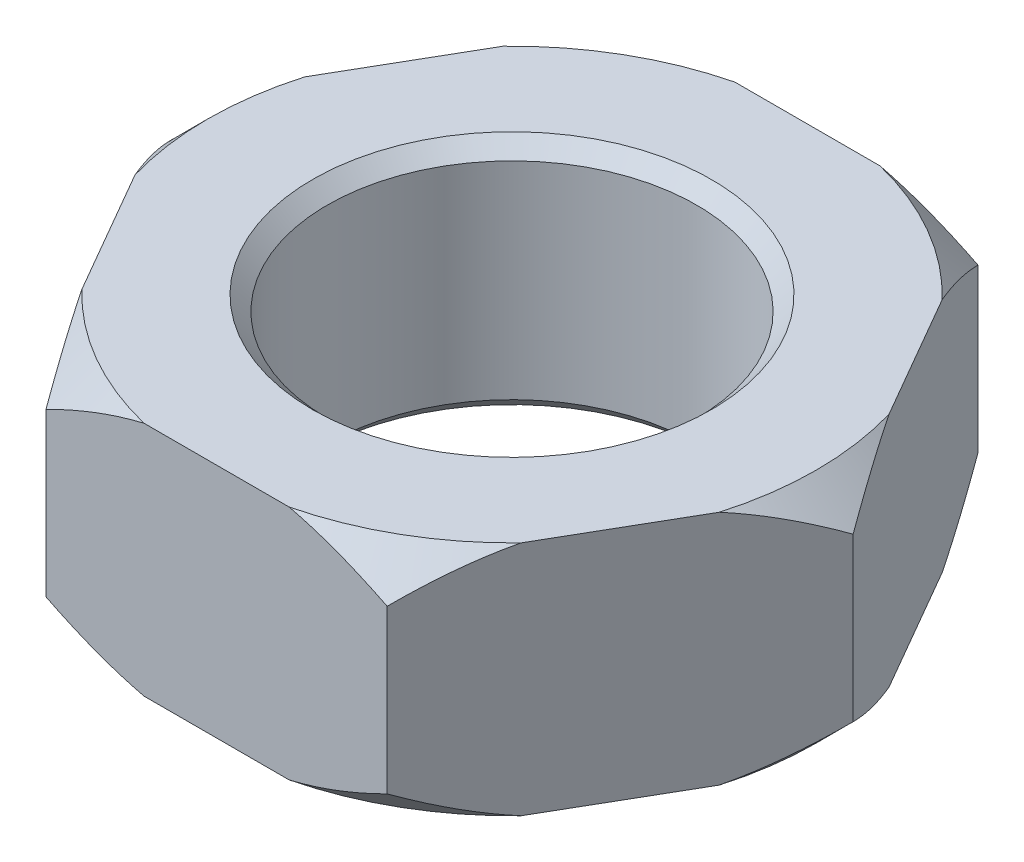
SolidWorks part; units mm, degrees
ref_plane "Спереди" through (0, 0, 0) normal (0, 0, 1) x (1, 0, 0)
ref_plane "Сверху" through (0, 0, 0) normal (0, 1, 0) x (1, 0, 0)
ref_plane "Справа" through (0, 0, 0) normal (1, 0, 0) x (0, 0, -1)
sketch "Эскиз1" plane through (0, 0, 0) normal (0, 1, 0) x (1, 0, 0)
  line L0 (-2.3094, 4) -> (2.3094, 4)
  line L1 (2.3094, 4) -> (4.6188, 0)
  line L2 (4.6188, 0) -> (2.3094, -4)
  line L3 (2.3094, -4) -> (-2.3094, -4)
  line L4 (-2.3094, -4) -> (-4.6188, 0)
  line L5 (-4.6188, 0) -> (-2.3094, 4)
  dimension "D5" = 4
  dimension "D2" = 120
  dimension "D3" = 120
  dimension "D4" = 120
  dimension "D6" = 4
  dimension "D7" = 4
  dimension "D8" = 4
  dimension "D9" = 4
  dimension "D10" = 120
  dimension "D11" = 4
extrude "Вытянуть1" add sketch "Эскиз1" against normal blind 3.2
sketch "Эскиз5" plane through (0, -3.2, 0) normal (0, -1, 0) x (1, 0, 0)
  circle A0 centre (0, 0) radius 2.5
  dimension "D1" = 5
extrude "Вырез-Вытянуть1" cut sketch "Эскиз5" against normal through all
ref_axis "Ось1" through (0, 0, 0) along (0, -1, 0)
ref_plane "Плоскость1" through (0, 0, 0) normal (0, 0, 1) x (1, 0, 0)
sketch "Эскиз4" plane through (0, 0, 0) normal (0, 0, 1) x (1, 0, 0)
  line L0 (-4.6188, -0.5) -> (-4.1188, 0)
  line L1 (-4.6188, -3.2) -> (-4.6188, 0) construction
  line L2 (-4.6188, 0) -> (-2.3094, 0) construction
  line L3 (-4.1188, 0) -> (-4.6188, 0)
  line L4 (-4.6188, 0) -> (-4.6188, -0.5)
  line L5 (-4.6188, -2.7) -> (-4.1188, -3.2)
  line L6 (-4.6188, -3.2) -> (-2.3094, -3.2) construction
  line L7 (-4.1188, -3.2) -> (-4.6188, -3.2)
  line L8 (-4.6188, -3.2) -> (-4.6188, -2.7)
  dimension "D1" = 0.5
  dimension "D2" = 0.5
  dimension "D3" = 0.5
  dimension "D4" = 0.5
revolve "Вырез-Повернуть1" cut sketch "Эскиз4" angle 360 about axis through (0, 0, 0) along (0, -1, 0)
chamfer "Фаска1" distance 0.2 angle 45 2 edges at (0, -3.2, -2.5) (0, 0, -2.5)
